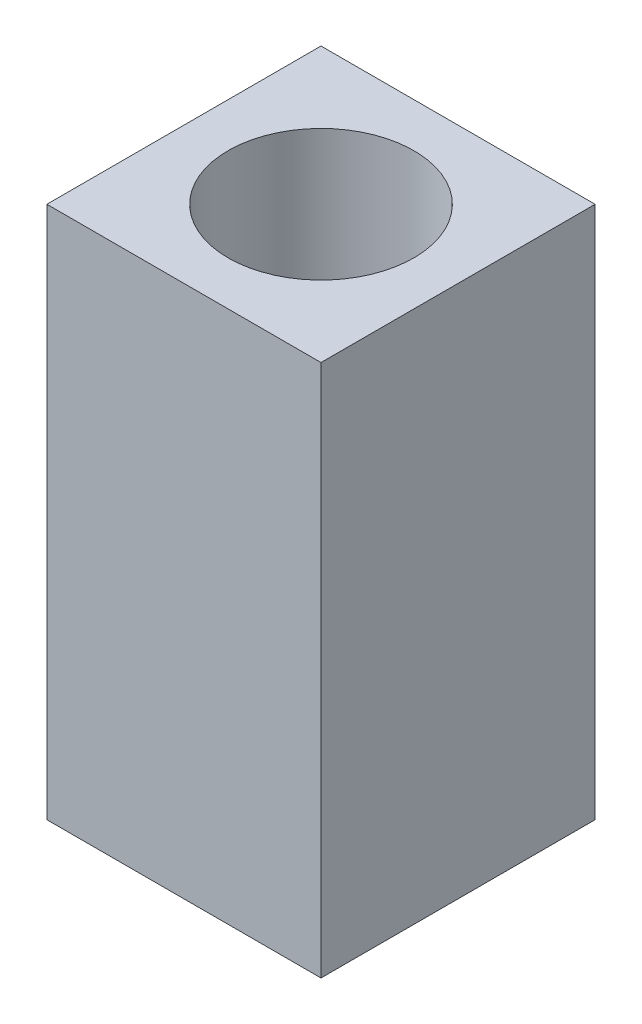
SolidWorks part; units mm, degrees
ref_plane "Front Plane" through (0, 0, 0) normal (0, 0, 1) x (1, 0, 0)
ref_plane "Top Plane" through (0, 0, 0) normal (0, 1, 0) x (1, 0, 0)
ref_plane "Right Plane" through (0, 0, 0) normal (1, 0, 0) x (0, 0, -1)
sketch "Sketch1" plane through (0, 0, 0) normal (0, 1, 0) x (1, 0, 0)
  line L0 (0, 18) -> (18, 0) construction
  line L1 (0, 0) -> (18, 0)
  line L2 (0, 0) -> (0, 18)
  line L3 (0, 18) -> (18, 18)
  line L4 (18, 0) -> (18, 18)
  circle A0 centre (9, 9) radius 6.1
  point P8 (9, 9)
  dimension "D3" = 12.2
  dimension "D1" = 18
  dimension "D2" = 18
extrude "Boss-Extrude1" add sketch "Sketch1" along normal blind 35
